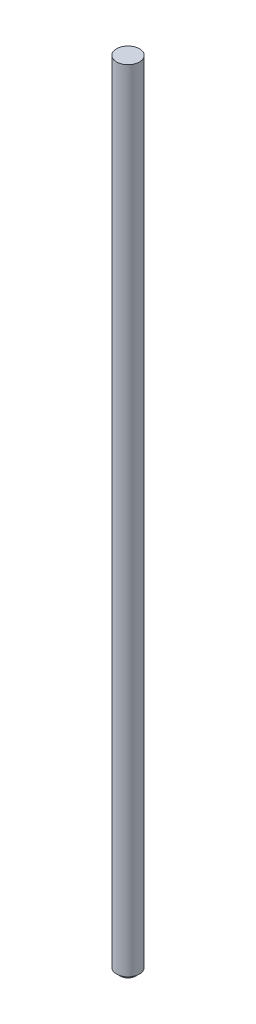
SolidWorks part; units mm, degrees
ref_plane "Front Plane" through (0, 0, 0) normal (0, 0, 1) x (1, 0, 0)
ref_plane "Top Plane" through (0, 0, 0) normal (0, 1, 0) x (1, 0, 0)
ref_plane "Right Plane" through (0, 0, 0) normal (1, 0, 0) x (0, 0, -1)
sketch "Sketch1" plane through (0, 0, 0) normal (0, 0, 1) x (1, 0, 0)
  line L0 (5.775, 1.752) -> (4, 1.752)
  line L1 (0, 0) -> (4, 0)
  line L2 (0, 0) -> (0, 400)
  line L3 (0, 400) -> (5.775, 400)
  line L4 (5.775, 1.752) -> (5.775, 400)
  line L5 (4, 1.752) -> (4, 0)
  dimension "D1" = 5.775
  dimension "D2" = 400
  dimension "D3" = 4
revolve "Revolve1" add sketch "Sketch1" angle 360 about L2
